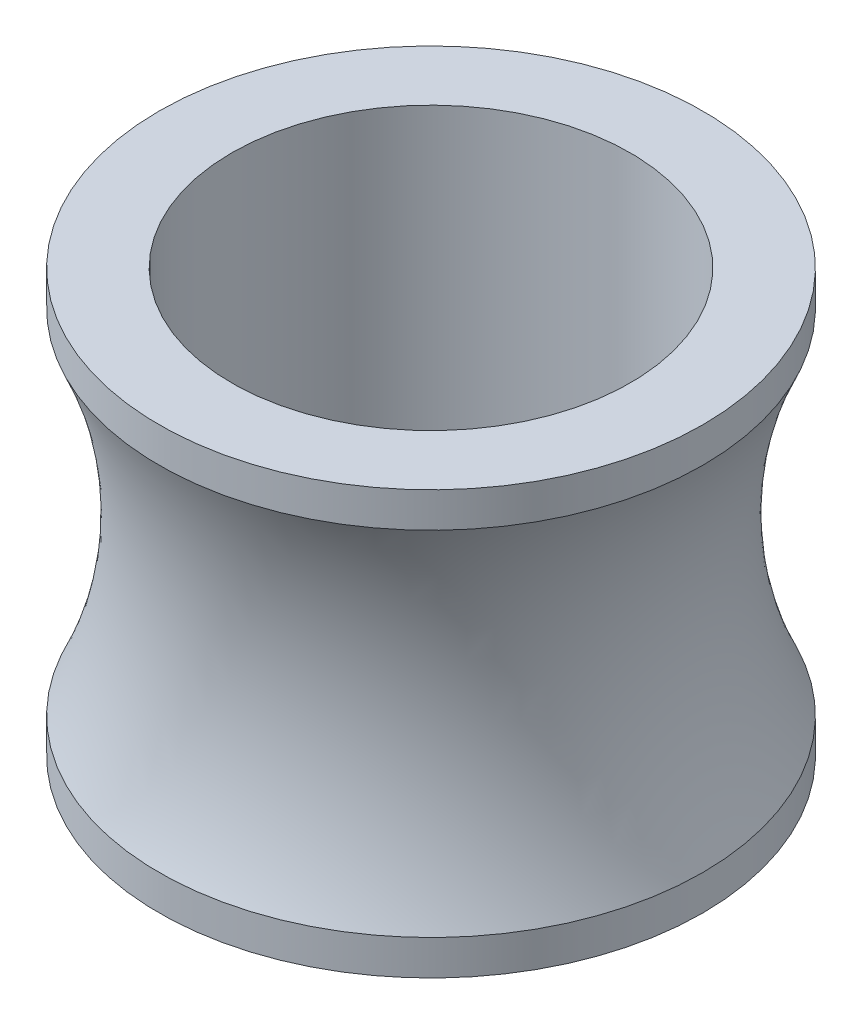
SolidWorks part; units mm, degrees
ref_plane "前视基准面" through (0, 0, 0) normal (0, 0, 1) x (1, 0, 0)
ref_plane "上视基准面" through (0, 0, 0) normal (0, 1, 0) x (1, 0, 0)
ref_plane "右视基准面" through (0, 0, 0) normal (1, 0, 0) x (0, 0, -1)
sketch "草图1" plane through (0, 0, 0) normal (0, 0, 1) x (1, 0, 0)
  line L0 (0, 35) -> (0, -35) construction
  line L1 (33, 35) -> (45, 35)
  line L2 (33, -35) -> (45, -35)
  line L3 (33, 35) -> (33, -35)
  line L4 (0, 35) -> (33, 35) construction
  line L5 (33, -35) -> (0, -35) construction
  line L6 (45, 35) -> (45, 29.1937)
  line L7 (45, -29.1937) -> (45, -35)
  arc A0 (45, 29.1937) -> (45, -29.1937) centre (108.6218, 0) ccw
  point P4 (0, 0)
  dimension "D1" = 140
  dimension "D2" = 70
  dimension "D3" = 5.8063
  dimension "D4" = 45
  dimension "D5" = 12
revolve "旋转2" add sketch "草图1" angle 360 about L0
